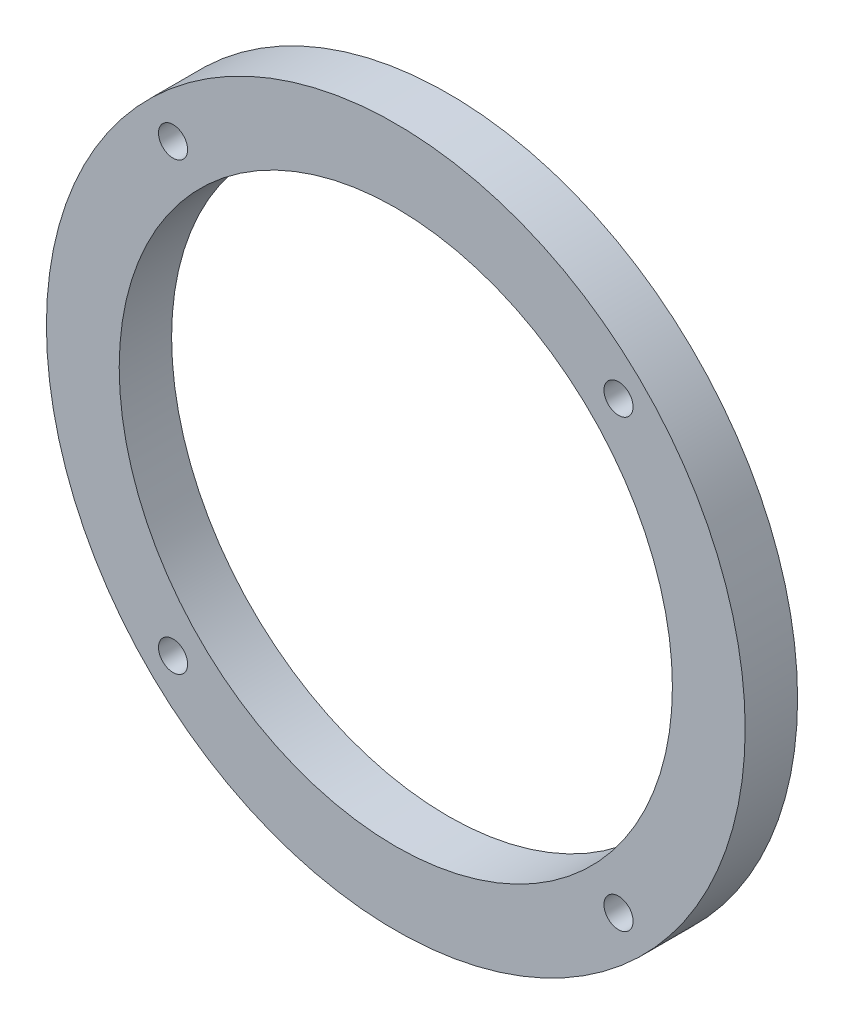
SolidWorks part; units mm, degrees
material "Q235A"
ref_plane "前视基准面" through (0, 0, 0) normal (0, 0, 1) x (1, 0, 0)
ref_plane "上视基准面" through (0, 0, 0) normal (0, 1, 0) x (1, 0, 0)
ref_plane "右视基准面" through (0, 0, 0) normal (1, 0, 0) x (0, 0, -1)
sketch "草图1" plane through (0, 0, 0) normal (0, 0, 1) x (1, 0, 0)
  circle A0 centre (0, 0) radius 47.5
  circle A1 centre (0, 0) radius 60
  dimension "D1" = 95
  dimension "D2" = 120
extrude "凸台-拉伸1" add sketch "草图1" along normal blind 9
sketch "草图2" plane through (0, 0, 9) normal (0, 0, 1) x (1, 0, 0)
  line L1 (-38.25, -38.25) -> (38.25, -38.25) construction
  line L2 (-38.25, -38.25) -> (-38.25, 38.25) construction
  line L3 (-38.25, 38.25) -> (38.25, 38.25) construction
  line L4 (38.25, -38.25) -> (38.25, 38.25) construction
  line L5 (-38.25, -38.25) -> (38.25, 38.25) construction
  line L6 (-38.25, 38.25) -> (38.25, -38.25) construction
  circle A1 centre (38.25, 38.25) radius 2.5
  circle A2 centre (38.25, -38.25) radius 2.5
  circle A3 centre (-38.25, -38.25) radius 2.5
  circle A4 centre (-38.25, 38.25) radius 2.5
  point P0 (0, 0)
  point P14 (0, 0)
  dimension "D1" = 4
  dimension "D2" = 76.5
  dimension "D4" = 5
  dimension "D5" = 5
  dimension "D3" = 76.5
extrude "切除-拉伸1" cut sketch "草图2" against normal blind 10
sketch "草图3" plane through (0, 0, 9) normal (0, 0, 1) x (1, 0, 0)
  circle A1 centre (38.25, -38.25) radius 2.5
  circle A2 centre (38.25, -38.25) radius 2.5
  circle A3 centre (38.25, 38.25) radius 2.5
  circle A4 centre (38.25, 38.25) radius 2.5
  circle A5 centre (0, 0) radius 47.5
  circle A6 centre (0, 0) radius 47.5
  circle A7 centre (-38.25, -38.25) radius 2.5
  circle A8 centre (-38.25, -38.25) radius 2.5
  circle A9 centre (-38.25, 38.25) radius 2.5
  circle A10 centre (-38.25, 38.25) radius 2.5
  circle A11 centre (0, 0) radius 60
  circle A12 centre (0, 0) radius 60
  dimension "D1" = 0
  dimension "D2" = 0
  dimension "D3" = 0
  dimension "D4" = 0
  dimension "D5" = 0
  dimension "D6" = 0
sketch "草图5" plane through (0, 0, 9) normal (0, 0, 1) x (1, 0, 0)
  line L0 (-38.25, 38.25) -> (38.25, -38.25) construction
